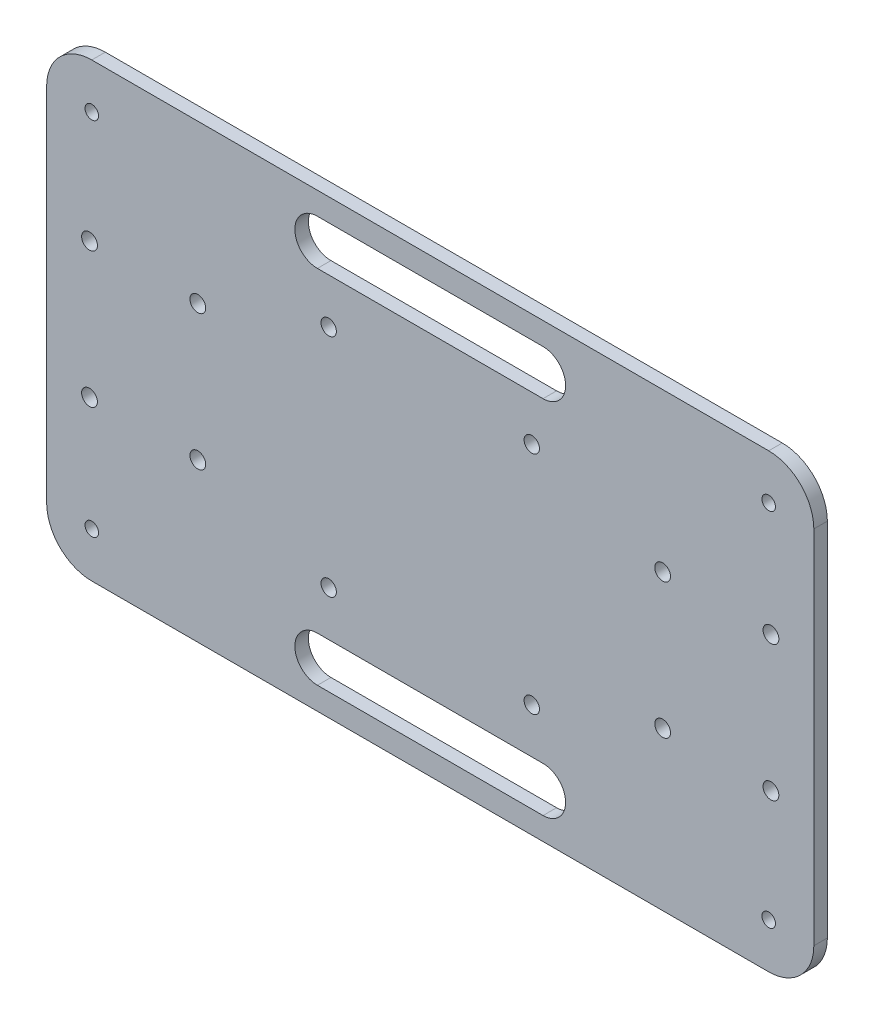
SolidWorks part; units mm, degrees
ref_plane "Front Plane" through (0, 0, 0) normal (0, 0, 1) x (1, 0, 0)
ref_plane "Top Plane" through (0, 0, 0) normal (0, 1, 0) x (1, 0, 0)
ref_plane "Right Plane" through (0, 0, 0) normal (1, 0, 0) x (0, 0, -1)
sketch "Sketch1" plane through (0, 0, 0) normal (0, 0, 1) x (1, 0, 0)
  line L0 (-85, 0) -> (85, 0) construction
  line L1 (-75, 50) -> (75, 50)
  line L2 (-85, 40) -> (-85, -40)
  line L3 (-75, -50) -> (75, -50)
  line L4 (85, 40) -> (85, -40)
  line L5 (-85, 50) -> (85, -50) construction
  line L6 (-85, -50) -> (85, 50) construction
  line L7 (0, 50) -> (0, -50) construction
  line L8 (-63.5, 20) -> (-63.5, -20) construction
  line L9 (-85, 20) -> (-42, 20)
  line L10 (-85, 20) -> (-85, -20)
  line L11 (-85, -20) -> (-42, -20)
  line L12 (-42, 20) -> (-42, -20)
  line L13 (-85, 20) -> (-42, -20) construction
  line L14 (-85, -20) -> (-42, 20) construction
  line L15 (85, -20) -> (42, -20)
  line L16 (42, 20) -> (42, -20)
  line L17 (85, 20) -> (42, 20)
  line L18 (85, 20) -> (85, -20)
  line L19 (-25, 40) -> (25, 40) construction
  line L20 (-25, 45) -> (25, 45)
  line L21 (-25, 35) -> (25, 35)
  line L22 (-25, -40) -> (25, -40) construction
  line L23 (-25, -45) -> (25, -45)
  line L24 (-25, -35) -> (25, -35)
  line L26 (-22.5, -25) -> (22.5, -25) construction
  line L27 (-22.5, -25) -> (-22.5, 25) construction
  line L28 (-22.5, 25) -> (22.5, 25) construction
  line L29 (22.5, -25) -> (22.5, 25) construction
  line L30 (-22.5, -25) -> (22.5, 25) construction
  line L31 (-22.5, 25) -> (22.5, -25) construction
  circle A0 centre (-75.5, 15) radius 1.75
  circle A1 centre (-75.5, -15) radius 1.75
  circle A2 centre (-51.5, -15) radius 1.75
  circle A3 centre (-51.5, 15) radius 1.75
  circle A4 centre (75.5, -15) radius 1.75
  circle A5 centre (51.5, -15) radius 1.75
  circle A6 centre (51.5, 15) radius 1.75
  circle A7 centre (75.5, 15) radius 1.75
  arc A8 (-85, -40) -> (-75, -50) centre (-75, -40) ccw
  arc A9 (75, -50) -> (85, -40) centre (75, -40) ccw
  arc A10 (75, 50) -> (85, 40) centre (75, 40) cw
  arc A11 (-85, 40) -> (-75, 50) centre (-75, 40) cw
  arc A12 (-25, 45) -> (-25, 35) centre (-25, 40) ccw
  arc A13 (25, 35) -> (25, 45) centre (25, 40) ccw
  arc A14 (-25, -45) -> (-25, -35) centre (-25, -40) cw
  arc A15 (25, -35) -> (25, -45) centre (25, -40) cw
  circle A16 centre (-75, -40) radius 1.5
  circle A17 centre (-75, 40) radius 1.5
  circle A18 centre (75, 40) radius 1.5
  circle A19 centre (75, -40) radius 1.5
  circle A34 centre (-22.5, 25) radius 1.7
  circle A35 centre (22.5, 25) radius 1.7
  circle A36 centre (22.5, -25) radius 1.7
  circle A37 centre (-22.5, -25) radius 1.7
  point P0 (0, 0)
  point P10 (-63.5, 0)
  point P51 (0, 40)
  point P58 (0, -40)
  point P72 (0, 0)
  dimension "D6" = 3.5
  dimension "D9" = 10
  dimension "D11" = 5
  dimension "D13" = 3
  dimension "D16" = 3
  dimension "D22" = 3.4
  dimension "D1" = 170
  dimension "D2" = 100
  dimension "D3" = 43
  dimension "D4" = 40
  dimension "D5" = 63.5
  dimension "D7" = 12
  dimension "D8" = 15
  dimension "D10" = 50
  dimension "D12" = 40
  dimension "D14" = 75
  dimension "D15" = 40
  dimension "D17" = 40
  dimension "D18" = 75
  dimension "D19" = 75
  dimension "D20" = 50
  dimension "D21" = 45
extrude "Boss-Extrude1" add sketch "Sketch1" along normal blind 3 contours A11 L2 L9 L12 L11 A8 L3 A9 L4 L15 L16 L17 A10 L1 A13 L21 A12 L20 L24 A15 L23 A14 | L12 L9 L2 L11 A1 A0 A2 A3 | L4 L17 L16 L15 A5 A4 A6 A7
